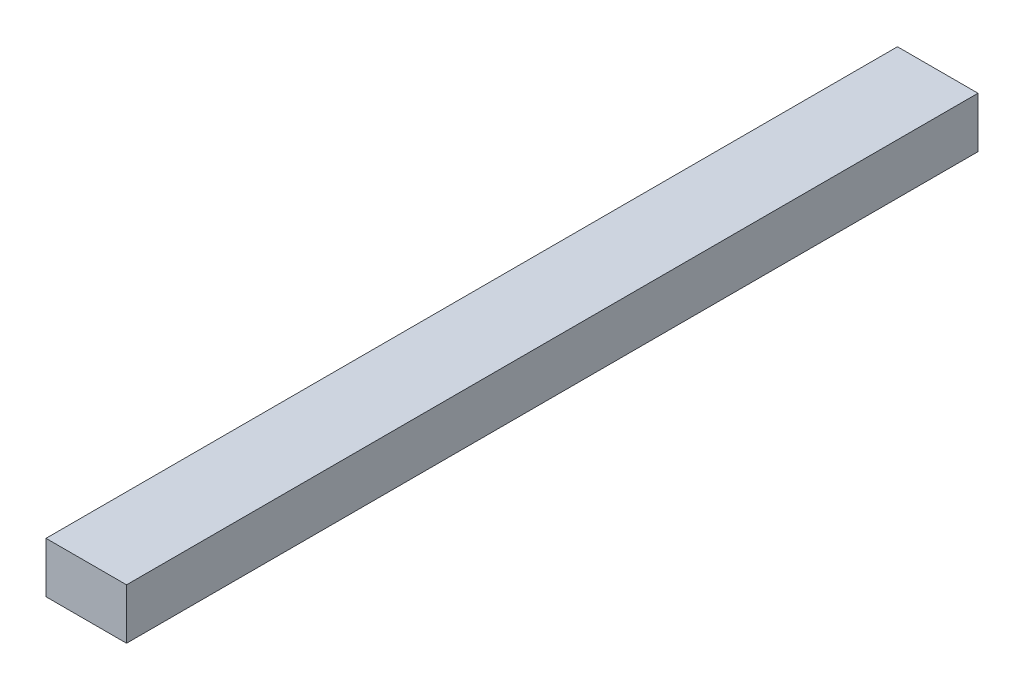
SolidWorks part; units mm, degrees
ref_plane "Front Plane" through (0, 0, 0) normal (0, 0, 1) x (1, 0, 0)
ref_plane "Top Plane" through (0, 0, 0) normal (0, 1, 0) x (1, 0, 0)
ref_plane "Right Plane" through (0, 0, 0) normal (1, 0, 0) x (0, 0, -1)
sketch "Sketch1" plane through (0, 0, 0) normal (0, 0, 1) x (1, 0, 0)
  line L7 (-35, -22) -> (35, -22)
  line L8 (-35, -22) -> (-35, 22)
  line L9 (-35, 22) -> (35, 22)
  line L10 (35, -22) -> (35, 22)
  line L11 (-35, -22) -> (35, 22) construction
  line L12 (-35, 22) -> (35, -22) construction
  point P10 (0, 0)
  dimension "D1" = 70
  dimension "D2" = 44
extrude "Boss-Extrude1" add sketch "Sketch1" along normal up to surface (590 mm away) and the other way up to surface (150 mm away)
